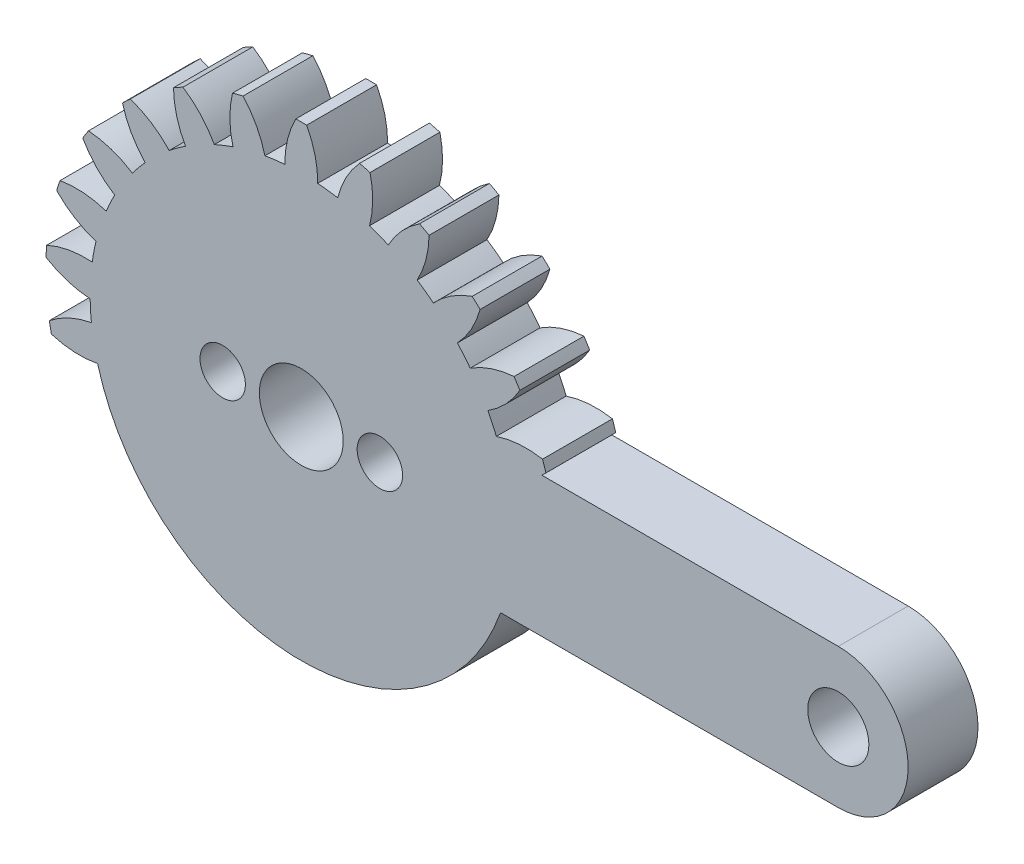
SolidWorks part; units mm, degrees
ref_plane "Front Plane" through (0, 0, 0) normal (0, 0, 1) x (1, 0, 0)
ref_plane "Top Plane" through (0, 0, 0) normal (0, 1, 0) x (1, 0, 0)
ref_plane "Right Plane" through (0, 0, 0) normal (1, 0, 0) x (0, 0, -1)
sketch "Sketch1" plane through (0, 0, 0) normal (0, 0, 1) x (1, 0, 0)
  line L0 (0, 0) -> (0, 14.63) construction
  line L1 (0, 0) -> (21.7469, 0) construction
  line L2 (11.4091, 4) -> (30.75, 4)
  line L3 (30.75, -4) -> (11.4091, -4)
  circle A0 centre (0, 0) radius 1.75
  circle A1 centre (0, 0) radius 12.09
  circle A2 centre (0, 0) radius 14.63
  arc A3 (0.31, 14.6267) -> (0.9431, 12.0532) centre (-4.4568, 12.0894) cw
  arc A4 (-0.31, 14.6267) -> (-0.9431, 12.0532) centre (4.4568, 12.0894) ccw
  arc A5 (3.3373, 14.2443) -> (2.084, 11.909) centre (7.3233, 10.6013) ccw
  arc A6 (3.9378, 14.0901) -> (3.911, 11.4399) centre (-1.3102, 12.818) cw
  arc A7 (6.7748, 12.9668) -> (4.9802, 11.0166) centre (9.7296, 8.447) ccw
  arc A8 (7.3181, 12.6681) -> (6.6331, 10.1079) centre (1.9186, 12.7411) cw
  arc A9 (9.7867, 10.8746) -> (7.5635, 9.432) centre (11.5246, 5.7619) ccw
  arc A10 (10.2387, 10.4502) -> (8.9384, 8.1408) centre (5.0269, 11.8637) cw
  arc A11 (12.1836, 8.0991) -> (9.6715, 7.2547) centre (12.5955, 2.7149) ccw
  arc A12 (12.5159, 7.5756) -> (10.6822, 5.6621) centre (7.8194, 10.2408) cw
  arc A13 (13.815, 4.8147) -> (11.1718, 4.6216) centre (12.875, -0.5028) ccw
  arc A14 (14.0066, 4.2251) -> (11.7547, 2.8277) centre (10.1205, 7.9745) cw
  arc A15 (14.5784, 1.2278) -> (11.9702, 1.6981) centre (12.3454, -3.6889) ccw
  arc A16 (14.6173, 0.609) -> (12.0886, -0.1844) centre (11.7857, 5.2071) cw
  arc A17 (14.4257, -2.4363) -> (12.0164, -1.3321) centre (11.0402, -6.6432) ccw
  arc A18 (14.3095, -3.0453) -> (11.6629, -3.1849) centre (12.7104, 2.1125) cw
  arc A19 (13.3666, -5.9473) -> (11.3076, -4.2786) centre (9.0412, -9.18) ccw
  arc A20 (13.1027, -6.5082) -> (10.5045, -5.9853) centre (12.8364, -1.1148) cw
  arc A21 (11.4677, -9.0846) -> (9.8883, -6.9563) centre (6.4742, -11.1401) ccw
  arc A22 (11.0725, -9.5623) -> (8.686, -8.4096) centre (12.1559, -4.2721) cw
  arc A23 (8.8482, -11.651) -> (7.8477, -9.1969) centre (3.5004, -12.4002) ccw
  arc A24 (8.3466, -12.0155) -> (6.3217, -10.3056) centre (10.7116, -7.1609) cw
  arc A25 (5.6727, -13.4855) -> (5.3139, -10.8596) centre (0.3066, -12.8811) ccw
  arc A26 (5.0962, -13.7137) -> (3.5602, -11.5539) centre (8.5942, -9.5998) cw
  arc A27 (2.1408, -14.4725) -> (2.4463, -11.8399) centre (-2.9064, -12.5527) ccw
  arc A28 (1.5257, -14.5502) -> (0.575, -12.0763) centre (5.9368, -11.4355) cw
  arc A29 (-1.5257, -14.5502) -> (-0.575, -12.0763) centre (-5.9368, -11.4355) ccw
  arc A30 (-2.1408, -14.4725) -> (-2.4463, -11.8399) centre (2.9064, -12.5527) cw
  arc A31 (-5.0962, -13.7137) -> (-3.5602, -11.5539) centre (-8.5942, -9.5998) ccw
  arc A32 (-5.6727, -13.4855) -> (-5.3139, -10.8596) centre (-0.3066, -12.8811) cw
  arc A33 (-8.3466, -12.0155) -> (-6.3217, -10.3056) centre (-10.7116, -7.1609) ccw
  arc A34 (-8.8482, -11.651) -> (-7.8477, -9.1969) centre (-3.5004, -12.4002) cw
  arc A35 (-11.0725, -9.5623) -> (-8.686, -8.4096) centre (-12.1559, -4.2721) ccw
  arc A36 (-11.4677, -9.0846) -> (-9.8883, -6.9563) centre (-6.4742, -11.1401) cw
  arc A37 (-13.1027, -6.5082) -> (-10.5045, -5.9853) centre (-12.8364, -1.1148) ccw
  arc A38 (-13.3666, -5.9473) -> (-11.3076, -4.2786) centre (-9.0412, -9.18) cw
  arc A39 (-14.3095, -3.0453) -> (-11.6629, -3.1849) centre (-12.7104, 2.1125) ccw
  arc A40 (-14.4257, -2.4363) -> (-12.0164, -1.3321) centre (-11.0402, -6.6432) cw
  arc A41 (-14.6173, 0.609) -> (-12.0886, -0.1844) centre (-11.7857, 5.2071) ccw
  arc A42 (-14.5784, 1.2278) -> (-11.9702, 1.6981) centre (-12.3454, -3.6889) cw
  arc A43 (-14.0066, 4.2251) -> (-11.7547, 2.8277) centre (-10.1205, 7.9745) ccw
  arc A44 (-13.815, 4.8147) -> (-11.1718, 4.6216) centre (-12.875, -0.5028) cw
  arc A45 (-12.5159, 7.5756) -> (-10.6822, 5.6621) centre (-7.8194, 10.2408) ccw
  arc A46 (-12.1836, 8.0991) -> (-9.6715, 7.2547) centre (-12.5955, 2.7149) cw
  arc A47 (-10.2387, 10.4502) -> (-8.9384, 8.1408) centre (-5.0269, 11.8637) ccw
  arc A48 (-9.7867, 10.8746) -> (-7.5635, 9.432) centre (-11.5246, 5.7619) cw
  arc A49 (-7.3181, 12.6681) -> (-6.6331, 10.1079) centre (-1.9186, 12.7411) ccw
  arc A50 (-6.7748, 12.9668) -> (-4.9802, 11.0166) centre (-9.7296, 8.447) cw
  arc A51 (30.75, 4) -> (30.75, -4) centre (30.75, 0) cw
  circle A52 centre (30.75, 0) radius 1.75
  arc A53 (-3.9378, 14.0901) -> (-3.911, 11.4399) centre (1.3102, 12.818) ccw
  arc A54 (-3.3373, 14.2443) -> (-2.084, 11.909) centre (-7.3233, 10.6013) cw
  point P153 (0, 0)
  dimension "D1" = 3.5
  dimension "D2" = 24.18
  dimension "D3" = 29.26
  dimension "D4" = 0.62
  dimension "D6" = 5.4
  dimension "D8" = 30.75
  dimension "D9" = 4
  dimension "D10" = 3.5
  dimension "D11" = 1.15
  dimension "D7" = 25
extrude "Boss-Extrude1" add sketch "Sketch1" along normal blind 4 contours A51 L2 A2 L3 A52 | A18 A2 A17 A1 | A2 A18 A1 L3 | A16 A2 A15 A1 | A14 L2 A1 | A14 A2 A13 A1 L2 | A12 A2 A11 A1 | A10 A2 A9 A1 | A17 A2 A16 A1 | A15 A2 L2 A14 A1 | A8 A2 A7 A1 | A6 A2 A5 A1 | A2 A4 A1 A3 | A54 A2 A53 A1 | A50 A2 A49 A1 | A48 A2 A47 A1 | A46 A2 A45 A1 | A44 A2 A43 A1 | A42 A2 A41 A1 | A40 A2 A39 A1 | A1 A3
sketch "Sketch2" plane through (0, 0, 4) normal (0, 0, 1) x (1, 0, 0)
  circle A0 centre (4.5, 0) radius 1.3
  circle A1 centre (-4.5, 0) radius 1.3
  circle A2 centre (0, 0) radius 2.4
  dimension "D1" = 4.5
  dimension "D3" = 2.6
  dimension "D4" = 4.8
  dimension "D2" = 9
extrude "Cut-Extrude1" cut sketch "Sketch2" against normal blind 20
